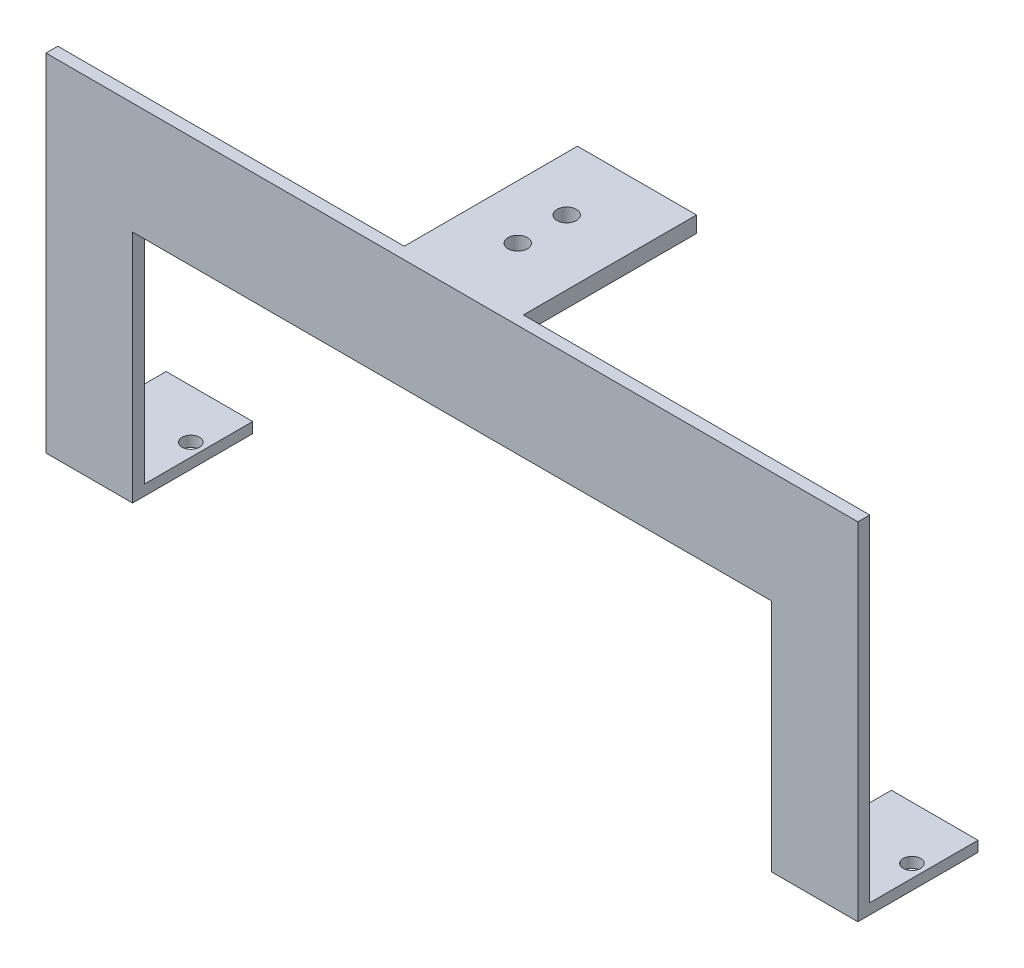
SolidWorks part; units mm, degrees
material "6061 Alloy"
ref_plane "Front Plane" through (0, 0, 0) normal (0, 0, 1) x (1, 0, 0)
ref_plane "Top Plane" through (0, 0, 0) normal (0, 1, 0) x (1, 0, 0)
ref_plane "Right Plane" through (0, 0, 0) normal (1, 0, 0) x (0, 0, -1)
sketch "Sketch1" plane through (0, 0, 0) normal (0, 0, 1) x (1, 0, 0)
  line L1 (-174.2545, -25.7291) -> (-148.8545, -25.7291)
  line L2 (-148.8545, -25.7291) -> (-148.8545, 43.1047)
  line L3 (-148.8545, 43.1047) -> (38.4705, 43.1047)
  line L4 (38.4705, 43.1047) -> (38.4705, -25.7291)
  line L5 (38.4705, -25.7291) -> (63.8705, -25.7291)
  line L9 (-174.2545, 75.8709) -> (63.8705, 75.8709)
  line L10 (-174.2545, 75.8709) -> (-174.2545, -25.7291)
  line L11 (63.8705, 75.8709) -> (63.8705, -25.7291)
  dimension "D1" = 238.125
  dimension "D2" = 25.4
  dimension "D3" = 25.4
  dimension "D4" = 101.6
  dimension "D5" = 101.6
extrude "Boss-Extrude1" add sketch "Sketch1" along normal blind 3.4798
sketch "Sketch2" plane through (0, 0, 0) normal (0, 0, -1) x (-1, 0, 0)
  line L0 (-38.4705, 43.1047) -> (-38.4705, -25.7291) construction
  line L1 (-63.8705, -25.7291) -> (-38.4705, -25.7291)
  line L2 (-63.8705, -25.7291) -> (-63.8705, -22.6303)
  line L3 (-63.8705, -22.6303) -> (-38.4705, -22.6303)
  line L4 (-38.4705, -25.7291) -> (-38.4705, -22.6303)
  dimension "D1" = 3.0988
extrude "Boss-Extrude2" add sketch "Sketch2" along normal blind 31.75
sketch "Sketch3" plane through (0, 0, 0) normal (0, 0, -1) x (-1, 0, 0)
  line L0 (148.8545, -25.7291) -> (148.8545, 43.1047) construction
  line L1 (148.8545, -22.6303) -> (174.2545, -22.6303)
  line L2 (148.8545, -22.6303) -> (148.8545, -25.7291)
  line L3 (148.8545, -25.7291) -> (174.2545, -25.7291)
  line L4 (174.2545, -22.6303) -> (174.2545, -25.7291)
  dimension "D1" = 3.0988
extrude "Boss-Extrude3" add sketch "Sketch3" along normal blind 31.75
sketch "Sketch4" plane through (0, 0, 0) normal (0, 0, -1) x (-1, 0, 0)
  line L0 (-63.8705, 75.8709) -> (174.2545, 75.8709) construction
  line L1 (37.7295, 75.8709) -> (72.6545, 75.8709)
  line L2 (37.7295, 75.8709) -> (37.7295, 71.161)
  line L3 (37.7295, 71.161) -> (72.6545, 71.161)
  line L4 (72.6545, 75.8709) -> (72.6545, 71.161)
  line L5 (-63.8705, -25.7291) -> (-63.8705, 75.8709) construction
  line L6 (174.2545, 75.8709) -> (174.2545, -22.6303) construction
  dimension "D1" = 101.6
  dimension "D2" = 101.6
extrude "Boss-Extrude4" add sketch "Sketch4" along normal blind 50.8
sketch "Sketch5" plane through (0, -25.7291, 0) normal (0, -1, 0) x (1, 0, 0)
  line L0 (38.4705, 3.4798) -> (38.4705, -31.75) construction
  circle A0 centre (42.2805, -15.3939) radius 2.54
  dimension "D1" = 3.81
  dimension "D2" = 5.08
extrude "Cut-Extrude1" cut sketch "Sketch5" against normal through all
sketch "Sketch6" plane through (0, -25.7291, 0) normal (0, -1, 0) x (1, 0, 0)
  line L0 (-174.2545, 3.4798) -> (-174.2545, -31.75) construction
  circle A0 centre (-170.4445, -17.1376) radius 2.54
  dimension "D1" = 3.81
  dimension "D2" = 5.08
extrude "Cut-Extrude2" cut sketch "Sketch6" against normal through all
sketch "Sketch7" plane through (0, -25.7291, 0) normal (0, -1, 0) x (1, 0, 0)
  line L0 (-148.8545, 3.4798) -> (-148.8545, -31.75) construction
  circle A0 centre (-152.6645, -17.4042) radius 2.54
  dimension "D1" = 3.81
  dimension "D2" = 5.08
extrude "Cut-Extrude3" cut sketch "Sketch7" against normal through all
sketch "Sketch8" plane through (0, -25.7291, 0) normal (0, -1, 0) x (-1, 0, 0)
  line L0 (-63.8705, -3.4798) -> (-63.8705, 31.75) construction
  circle A0 centre (-60.0605, 16.1782) radius 2.54
  dimension "D1" = 5.08
  dimension "D2" = 3.81
extrude "Cut-Extrude4" cut sketch "Sketch8" against normal blind 50.8
sketch "Sketch9" plane through (0, 75.8709, 0) normal (0, 1, 0) x (1, 0, 0)
  line L0 (-37.7295, 50.8) -> (-37.7295, 0) construction
  circle A0 centre (-56.7795, 17.4132) radius 2.843
  dimension "D1" = 19.05
extrude "Cut-Extrude5" cut sketch "Sketch9" against normal through all
sketch "Sketch10" plane through (0, 75.8709, 0) normal (0, 1, 0) x (1, 0, 0)
  line L0 (-72.6545, 50.8) -> (-37.7295, 50.8) construction
  line L1 (-37.7295, 50.8) -> (-37.7295, 0) construction
  circle A0 centre (-56.7795, 31.75) radius 2.847
  dimension "D1" = 19.05
  dimension "D2" = 19.05
extrude "Cut-Extrude6" cut sketch "Sketch10" against normal blind 50.8
